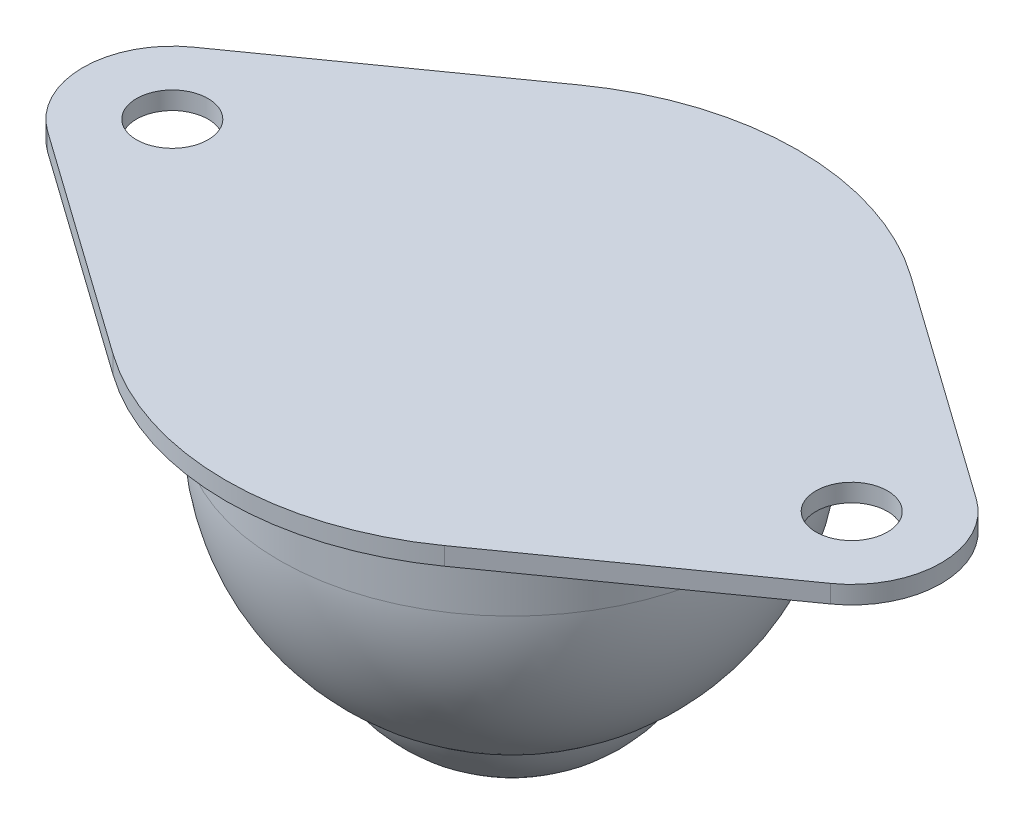
SolidWorks part; units mm, degrees
ref_plane "Front Plane" through (0, 0, 0) normal (0, 0, 1) x (1, 0, 0)
ref_plane "Top Plane" through (0, 0, 0) normal (0, 1, 0) x (1, 0, 0)
ref_plane "Right Plane" through (0, 0, 0) normal (1, 0, 0) x (0, 0, -1)
sketch "Sketch1" plane through (0, 0, 0) normal (0, 1, 0) x (1, 0, 0)
  line L0 (0, 8.5) -> (0, -8.5)
  arc A0 (0, -8.5) -> (0, 8.5) centre (0, 0) ccw
  dimension "D1" = 17
revolve "Revolve1" add sketch "Sketch1" angle 360 about L0
sketch "Sketch2" plane through (0, 0, 0) normal (0, 0, 1) x (1, 0, 0)
  line L0 (13, 6.6184) -> (13, 11)
  line L1 (13, 11) -> (0, 11)
  line L2 (0, 11) -> (0, 10)
  line L3 (0, 10) -> (12, 10)
  line L4 (12, 10) -> (12, 6.6184)
  circle A0 centre (0, 0) radius 8.5 construction
  arc A1 (7.5, -4) -> (13, 6.6184) centre (0, 6.6184) ccw
  arc A2 (8.2336, -2.1113) -> (12, 6.6184) centre (0, 6.6184) ccw
  arc A3 (7.5, -4) -> (8.2336, -2.1113) centre (0, 0) ccw
  dimension "D1" = 1
  dimension "D2" = 13
  dimension "D3" = 15
  dimension "D4" = 1
  dimension "D5" = 7.5
revolve "Revolve2" add sketch "Sketch2" angle 360 about L2
sketch "Sketch3" plane through (0, 11, 0) normal (0, 1, 0) x (1, 0, 0)
  line L0 (0, 16) -> (0, -16) construction
  line L1 (-21.8947, 4.0768) -> (-9.2632, 13.0458)
  line L2 (0, 0) -> (-10.0645, 0) construction
  line L3 (-21.8947, -4.0768) -> (-9.2632, -13.0458)
  line L4 (21.8947, -4.0768) -> (9.2632, -13.0458)
  line L5 (21.8947, 4.0768) -> (9.2632, 13.0458)
  arc A0 (-9.2632, -13.0458) -> (9.2632, -13.0458) centre (0, 0) ccw
  circle A1 centre (-19, 0) radius 2
  arc A2 (-21.8947, 4.0768) -> (-21.8947, -4.0768) centre (-19, 0) ccw
  arc A3 (9.2632, 13.0458) -> (-9.2632, 13.0458) centre (0, 0) ccw
  circle A4 centre (19, 0) radius 2
  arc A5 (21.8947, 4.0768) -> (21.8947, -4.0768) centre (19, 0) cw
  dimension "D1" = 4
  dimension "D2" = 5
  dimension "D4" = 19
extrude "Boss-Extrude1" add sketch "Sketch3" along normal blind 1
